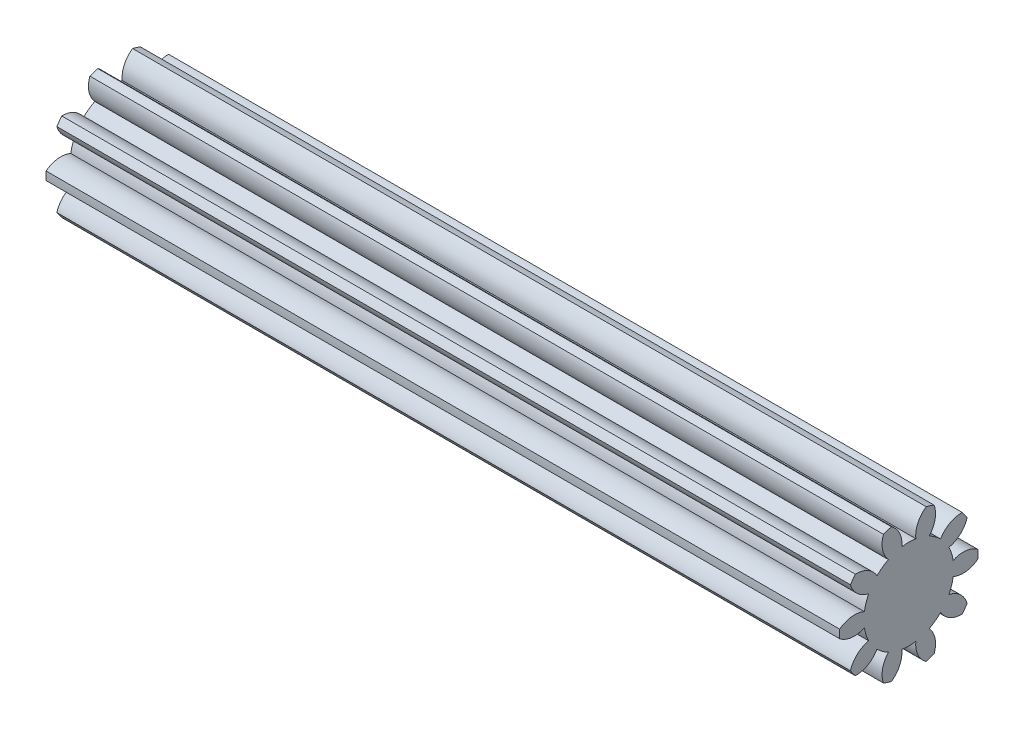
SolidWorks part; units mm, degrees
ref_plane "Plane1" through (0, 0, 0) normal (0, 0, 1) x (1, 0, 0)
ref_plane "Plane2" through (0, 0, 0) normal (0, 1, 0) x (1, 0, 0)
ref_plane "Plane3" through (0, 0, 0) normal (1, 0, 0) x (0, 0, -1)
sketch "HoldingSke" plane through (0, 0, 0) normal (0, 1, 0) x (1, 0, 0)
  line L0 (0, 0) -> (0.4924, -0.0868)
  line L1 (-15, 0) -> (100, 0) construction
  line L2 (0, 0) -> (-2.1039, 2.3779)
  line L3 (0, 0) -> (-11.863, 4.5341)
  line L4 (0, 0) -> (8.5048, 1.4996)
  line L5 (0, 0) -> (-46.8476, -17.4728)
  line L6 (0, 0) -> (-9.9476, -6.7116)
  line L7 (-2.1039, 2.3779) -> (8.6586, 51.2059)
  line L8 (-76.2, 54.61) -> (-76.1, 54.61)
  line L9 (-71.009, 38.7566) -> (-53.1078, 45.2721)
  line L10 (-76.2, 71.12) -> (104.1128, 71.12)
  line L11 (0, 0) -> (-12, 0)
  line L12 (-76.2, 101.6) -> (-76.133, 101.6)
  line L13 (24.9733, 27.94) -> (52.9518, 28.4284)
  line L14 (24.9733, 27.94) -> (24.9743, 27.94)
  line L15 (24.9733, 27.94) -> (100.4006, 29.5858)
  line L16 (-63.627, -2) -> (-12.827, -2)
  circle A0 centre (0, 0) radius 0.4
  circle A1 centre (0, 0) radius 7.499
  circle A2 centre (0, 0) radius 37.5
  circle A3 centre (0, 0) radius 0.4
  dimension "MHD" = 14.998
  dimension "Hub_dia" = 75
  dimension "Bore" = 0.8
  dimension "MBD" = 0.8
  dimension "Num_teeth" = 10
  dimension "Pitch" = 0.5
  dimension "Overall_len" = 50
  dimension "Show_teeth" = 10
  dimension "Thickness" = 12
  dimension "OAL" = 50.0001
  dimension "T_dim" = 0.1
  dimension "Ap" = 20
  dimension "H" = 19.05
  dimension "Pitch_radius" = 180.3128
  dimension "Width" = 12
  dimension "Backlash" = 0.067
  dimension "Addendum_fac" = 1
  dimension "Dedendum_fac" = 1.25
  dimension "Clearance_fac" = 0.25
  dimension "Dedendum_add" = 0.001
  dimension "Module" = 2
sketch "BasProSke" plane through (0, 0, 0) normal (0, 1, 0) x (1, 0, 0)
  line L0 (-10, 0) -> (60, 0) construction
  line L1 (0, 0) -> (0, 12)
  line L2 (0, 0) -> (132.288, 0)
  line L3 (132.288, 0) -> (132.288, 12)
  line L4 (132.288, 12) -> (0, 12)
  dimension "Thickness" = 132.288
  dimension "Diameter" = 24
revolve "Base-Revolve" add sketch "BasProSke" angle 360 about L0
sketch "TooCutSke" plane through (0, 0, 0) normal (1, 0, 0) x (0, 0, -1)
  line L1 (0, 0) -> (0, 107) construction
  line L2 (0, 0) -> (-1.6814, 9.8576) construction
  line L3 (0, 0) -> (-6.1153, 18.8209) construction
  line L4 (-1.6814, 9.8576) -> (-3.0576, 9.4105) construction
  arc A0 (1.1737, 7.4066) -> (-1.1737, 7.4066) centre (0, 0) ccw
  arc A1 (3.4979, 11.5054) -> (-3.4979, 11.5054) centre (0, 0) ccw
  circle A2 centre (0, 0) radius 10 construction
  circle A3 centre (0, 0) radius 9.3969 construction
  arc A4 (-1.1737, 7.4066) -> (-3.4979, 11.5054) centre (-5.1477, 7.8615) ccw
  arc A5 (3.4979, 11.5054) -> (1.1737, 7.4066) centre (5.1477, 7.8615) ccw
  dimension "Root_dia" = 14.998
  dimension "Overcut_dia" = 24.0508
  dimension "Pitch_dia" = 20
  dimension "Base_dia" = 18.7939
  dimension "Flank_rad" = 4
  dimension "Half_ang" = 18
  dimension "Half_CT" = 1.4471
extrude "ToothCut" cut sketch "TooCutSke" along normal through all
fillet "Breaks" [suppressed] radius 0.04
fillet "RootFillets" [suppressed] radius 0.501
pattern_circular "TeethCuts" count 10 every 36 about axis through (-10, 0, 0) along (1, 0, 0) of "ToothCut", "RootFillets", "Breaks"
sketch "HubNeaOneSke" plane through (0, 0, 0) normal (-1, 0, 0) x (0, 0, 1)
  circle A0 centre (0, 0) radius 7.499
  dimension "Diameter" = 14.998
extrude "HubNearOne" [suppressed] add sketch "HubNeaOneSke" along normal blind 38.0001
sketch "HubNeaBotSke" plane through (0, 0, 0) normal (-1, 0, 0) x (0, 0, 1)
  circle A0 centre (0, 0) radius 7.499
  dimension "Diameter" = 14.998
extrude "HubNearBoth" [suppressed] add sketch "HubNeaBotSke" along normal blind 19
ref_plane "FarPln" through (132.288, 0, 0) normal (1, 0, 0) x (0, 0, -1)
sketch "HubFarSke" plane through (132.288, 0, 0) normal (1, 0, 0) x (0, 0, -1)
  circle A0 centre (0, 0) radius 7.499
  dimension "Diameter" = 14.998
extrude "HubFar" [suppressed] add sketch "HubFarSke" along normal blind 19
sketch "BorSke" plane through (0, 0, 0) normal (1, 0, 0) x (0, 0, -1)
  circle A0 centre (0, 0) radius 0.4
  dimension "Diameter" = 0.8
extrude "Bore" cut sketch "BorSke" along normal mid plane 100.0001
sketch "KeySke" plane through (0, 0, 0) normal (1, 0, 0) x (0, 0, -1)
  line L0 (-0.05, 0) -> (-0.05, 0.5)
  line L1 (-0.05, 0.5) -> (0.05, 0.5)
  line L2 (0.05, 0.5) -> (0.05, 0)
  line L3 (0, 0) -> (0, 34) construction
  line L4 (-0.05, 0) -> (0.05, 0)
  dimension "Offset" = 0.5
  dimension "Width" = 0.1
extrude "Keyway" [suppressed] cut sketch "KeySke" along normal mid plane 100.0001
pattern_circular "Keyway2" [suppressed] count 2 every 90 about axis through (-10, 0, 0) along (1, 0, 0)
sketch "Sketch1" plane through (132.288, 0, 0) normal (1, 0, 0) x (0, 0, -1)
  circle A0 centre (0, 0) radius 11.538
  circle A1 centre (0, 0) radius 15.1998
extrude "Cut-Extrude1" cut sketch "Sketch1" against normal through all
scale "Scale1" scale about origin uniform scaling yes scale factor 0.4
equation "' \"Module@HoldingSke\" = 6.35"
equation "' \"Num_teeth@HoldingSke\" = 12"
equation "' \"Ap@HoldingSke\" =  20"
equation "' \"Ap@HoldingSke\" = 20"
equation "' \"Width@HoldingSke\" = 0.5 * 25.4"
equation "' \"Hub_dia@HoldingSke\"= 1 * 25.4"
equation "' \"Hub_dia@HoldingSke\" = 1 * 25.4"
equation "' \"Overall_len@HoldingSke\" = 1.0 * 25.4"
equation "' \"Bore@HoldingSke\" = 0.75 * 25.4"
equation "' \"T_dim@HoldingSke\" = 0.1 * 25.4"
equation "' \"Width@KeySke\" = 0.25 * 25.4"
equation "' \"Show_teeth@HoldingSke\" = 13"
equation "' \"Backlash@HoldingSke\" = 0.009 * 25.4"
equation "' \"Addendum_fac@HoldingSke\" = 1.0"
equation "' \"Dedendum_fac@HoldingSke\" = 1.25"
equation "' \"Dedendum_add@HoldingSke\" = 0.00005 * 25.4"
equation "' \"Clearance_fac@HoldingSke\" = 0.25"
equation "\"Pitch@HoldingSke\" = 1 / \"Module@HoldingSke\""
equation "\"Overcut_dia@TooCutSke\" = (\"Num_teeth@HoldingSke\" + 2 * \"Addendum_fac@HoldingSke\") / \"Pitch@HoldingSke\" + 0.002 * 25.4"
equation "\"Pitch_dia@TooCutSke\" = \"Num_teeth@HoldingSke\" / \"Pitch@HoldingSke\""
equation "\"Base_dia@TooCutSke\" = \"Num_teeth@HoldingSke\" / \"Pitch@HoldingSke\" * cos((\"Ap@HoldingSke\"  * 3.14159265 / 180))"
equation "\"Root_dia@TooCutSke\" = (\"Num_teeth@HoldingSke\" + 2) / \"Pitch@HoldingSke\" - 2 * (\"Addendum_fac@HoldingSke\" + \"Dedendum_fac@HoldingSke\") / \"Pitch@HoldingSke\" - \"Dedendum_add@HoldingSke\" * 2"
equation "\"Half_ang@TooCutSke\" = 180 / \"Num_teeth@HoldingSke\""
equation "\"Half_CT@TooCutSke\" = \"Num_teeth@HoldingSke\" / \"Pitch@HoldingSke\" * sin((3.14159265 / 2 / \"Num_teeth@HoldingSke\")) / 2 - 7 * \"Backlash@HoldingSke\" / 4"
equation "\"Flank_rad@TooCutSke\" = \"Num_teeth@HoldingSke\" / \"Pitch@HoldingSke\" / 5"
equation "\"Radius@RootFillets\" = \"Clearance_fac@HoldingSke\" / \"Pitch@HoldingSke\" + \"Dedendum_add@HoldingSke\""
equation "\"Break_rad@Breaks\" = 0.02 / \"Pitch@HoldingSke\""
equation "\"Thickness@HoldingSke\" = \"Width@HoldingSke\""
equation "\"OAL@HoldingSke\" = \"Thickness@HoldingSke\""
equation "\"MHD@HoldingSke\" = (\"Num_teeth@HoldingSke\" + 2) / \"Pitch@HoldingSke\" - 2 * (\"Addendum_fac@HoldingSke\" + \"Dedendum_fac@HoldingSke\")  / \"Pitch@HoldingSke\" - \"Dedendum_add@HoldingSke\" * 2"
equation "\"MBD@HoldingSke\" = (\"Num_teeth@HoldingSke\" + 2) / \"Pitch@HoldingSke\" - 2 * (\"Addendum_fac@HoldingSke\" + \"Dedendum_fac@HoldingSke\")  / \"Pitch@HoldingSke\" - \"Dedendum_add@HoldingSke\" * 2 - 0.002 * 25.4"
equation "\"MHD@HoldingSke\" = ((sgn( \"MHD@HoldingSke\" - \"Hub_dia@HoldingSke\" )-1)*( \"MHD@HoldingSke\" - \"Hub_dia@HoldingSke\" ))/-2+ \"Hub_dia@HoldingSke\""
equation "\"MBD@HoldingSke\" = ((sgn( \"MBD@HoldingSke\" - \"Bore@HoldingSke\" )-1)*( \"MBD@HoldingSke\" - \"Bore@HoldingSke\" ))/-2+ \"Bore@HoldingSke\""
equation "\"OAL@HoldingSke\" = ((sgn( \"OAL@HoldingSke\" - \"Overall_len@HoldingSke\" )+1)*( \"OAL@HoldingSke\" - \"Overall_len@HoldingSke\" ))/2 + \"Overall_len@HoldingSke\" + 0.000002 * 25.4"
equation "\"Num_teeth@TeethCuts\" = int( \"Show_teeth@HoldingSke\" ) + 1"
equation "\"Num_teeth@TeethCuts\" = ((sgn( \"Num_teeth@TeethCuts\" - \"Num_teeth@HoldingSke\" )-1)*( \"Num_teeth@TeethCuts\" - \"Num_teeth@HoldingSke\" ))/-2+ \"Num_teeth@HoldingSke\""
equation "\"Num_teeth@TeethCuts\" = ((sgn( \"Num_teeth@TeethCuts\" - 2.0)+1)*( \"Num_teeth@TeethCuts\" - 2.0))/2 +2.0"
equation "\"Angle@TeethCuts\" = 360.0 / \"Num_teeth@HoldingSke\""
equation "\"Diameter@BasProSke\" = (\"Num_teeth@HoldingSke\" + 2 * \"Addendum_fac@HoldingSke\") / \"Pitch@HoldingSke\""
equation "' \"Fillet_rad@BasProSke\" =  \"Thickness@HoldingSke\" * 0.05"
equation "' \"Fillet_rad@BasProSke\" = \"Thickness@HoldingSke\" * 0.05"
equation "\"MHD@HoldingSke\" = ((sgn( \"MHD@HoldingSke\" - \"Root_dia@TooCutSke\" )-1)*( \"MHD@HoldingSke\" - \"Root_dia@TooCutSke\" ))/-2+ \"Root_dia@TooCutSke\""
equation "\"Diameter@HubNeaOneSke\" = \"MHD@HoldingSke\""
equation "\"Length@HubNearOne\" = \"OAL@HoldingSke\" - \"Thickness@BasProSke\""
equation "\"Diameter@HubNeaBotSke\" = \"MHD@HoldingSke\""
equation "\"Length@HubNearBoth\" = ( \"OAL@HoldingSke\" - \"Thickness@BasProSke\" ) / 2.0"
equation "\"Thickness@FarPln\" = \"Thickness@BasProSke\""
equation "\"Diameter@HubFarSke\" = \"MHD@HoldingSke\""
equation "\"Length@HubFar\" = ( \"OAL@HoldingSke\" - \"Thickness@BasProSke\" ) / 2.0"
equation "\"Diameter@BorSke\" = \"MBD@HoldingSke\""
equation "\"D1@Bore\" = \"OAL@HoldingSke\" * 2.0"
equation "\"D1@Keyway\" = \"OAL@HoldingSke\" * 2.0"
equation "\"Offset@KeySke\" = \"T_dim@HoldingSke\" + \"MBD@HoldingSke\" / 2.0"
